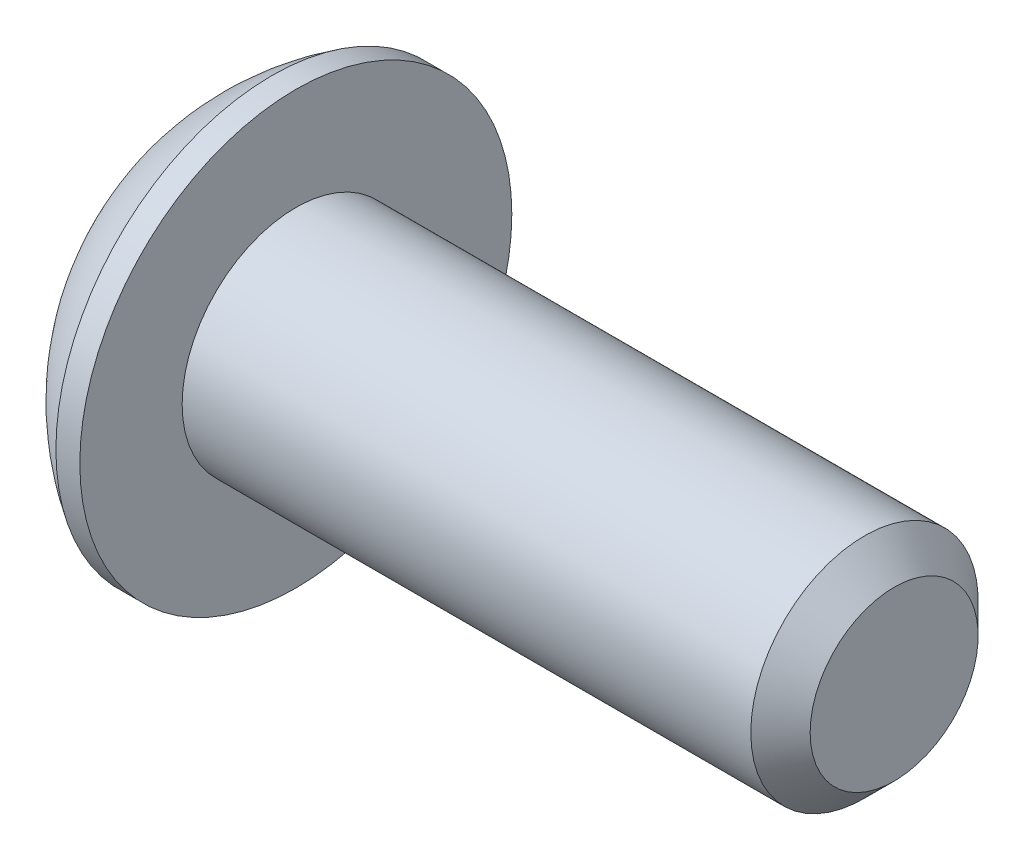
SolidWorks part; units mm, degrees
ref_plane "Plane1" through (0, 0, 0) normal (0, 0, 1) x (1, 0, 0)
ref_plane "Plane2" through (0, 0, 0) normal (0, 1, 0) x (1, 0, 0)
ref_plane "Plane3" through (0, 0, 0) normal (1, 0, 0) x (0, 0, -1)
sketch "BodySke" plane through (0, 0, 0) normal (0, 0, 1) x (1, 0, 0)
  line L0 (15.2654, 0) -> (15.2654, 1.7831)
  line L1 (14.6355, 2.413) -> (2.5654, 2.413)
  line L2 (2.5654, 2.413) -> (2.5654, 4.5847)
  line L3 (2.5654, 4.5847) -> (2.0574, 4.5847)
  line L4 (0, 0) -> (101.6, 0) construction
  line L5 (2.5654, -4.5847) -> (2.0574, -4.5847) construction
  line L6 (55.6768, -2.413) -> (2.5654, -2.413) construction
  line L7 (15.2654, 0) -> (0, 0)
  line L8 (0, 2.2923) -> (0, -2.2923) construction
  line L9 (0, 0) -> (0, 2.2923)
  line L10 (15.2654, 1.7831) -> (14.6355, 2.413)
  line L11 (15.2654, -1.7831) -> (14.6355, -2.413) construction
  line L12 (3.6246, 9.525) -> (3.6246, -2.413) construction
  line L13 (2.5654, 9.525) -> (2.5654, -2.413) construction
  arc A1 (0, 2.2923) -> (2.0574, 4.5847) centre (4.8599, 0) cw
  dimension "D1" = 4.5847
  dimension "Diameter" = 4.826
  dimension "Length" = 12.7
  dimension "Head_dia" = 9.1694
  dimension "Head_ht" = 2.5654
  dimension "Head_side_ht" = 0.508
  dimension "Minor_dia" = 3.5662
  dimension "Body_ch_ang" = 45
  dimension "Advance" = 1.0592
  dimension "Thread_nom" = 12.7
revolve "BaseBody" add sketch "BodySke" angle 360 about L4
cosmetic thread "ThreadCosmetic" [suppressed] parameters "Thread_length"=11.6408, "Thread_minor"=3.5662
sketch "Sketch2" plane through (0, 0, 0) normal (0, 0, 1) x (1, 0, 0)
  line L0 (0, 1.5875) -> (1.778, 1.5875)
  line L1 (1.778, 1.5875) -> (2.6945, 0)
  line L3 (2.6945, 0) -> (0, 0)
  line L4 (0, 0) -> (0, 1.5875)
  line L5 (0, -1.5875) -> (1.778, -1.5875) construction
  line L6 (0, 0) -> (47.625, 0) construction
  dimension "D2" = 60
  dimension "PreBroach_depth" = 1.778
  dimension "PreBroach_dia" = 3.175
revolve "PreBroach" cut sketch "Sketch2" angle 360 about L6
sketch "Sketch3" plane through (0, 0, 0) normal (1, 0, 0) x (0, 0, -1)
  line L0 (-1.5875, -0.9165) -> (-1.5875, 0.9165)
  line L1 (-1.5875, 0.9165) -> (0, 1.8331)
  line L2 (0, 1.8331) -> (1.5875, 0.9165)
  line L3 (1.5875, 0.9165) -> (1.5875, -0.9165)
  line L4 (1.5875, -0.9165) -> (0, -1.8331)
  line L5 (0, -1.8331) -> (-1.5875, -0.9165)
  dimension "D1" = 1.5875
  dimension "D2" = 1.5875
  dimension "D3" = 3.175
  dimension "Hex_size" = 3.175
extrude "Hex" cut sketch "Sketch3" along normal blind 1.778
sketch "Sketch4" plane through (0, 9.525, 0) normal (1, 0, 0) x (0, 0, -1)
  line L0 (0, -9.525) -> (1.8923, -9.525)
  line L1 (0, -9.525) -> (6.1484, -5.9752) construction
  line L2 (0, -9.525) -> (0.9461, -7.8862)
  line L3 (1.5663, -9.09) -> (1.8037, -8.9529)
  line L4 (1.1599, -8.3861) -> (1.3973, -8.249)
  arc A0 (1.5663, -9.09) -> (1.1599, -8.3861) centre (0, -9.525) ccw
  arc A1 (1.8923, -9.525) -> (1.8037, -8.9529) centre (0, -9.525) ccw
  arc A2 (0.9461, -7.8862) -> (1.3973, -8.249) centre (0, -9.525) cw
  dimension "D1" = 30
  dimension "Spline_n_dim" = 3.2512
  dimension "Spline_m_dim" = 3.7846
  dimension "D2" = 60
  dimension "D3" = 0.4064
  dimension "Spline_p_dim" = 0.8128
extrude "Spline" [suppressed] cut sketch "Sketch4" along normal blind 1.778
pattern_circular "CirPattern1" [suppressed] count 6 every 60 about axis through (0, 0, 0) along (1, 0, 0)
sketch "ThdSchSke" plane through (0, 0, 0) normal (0, 0, 1) x (1, 0, 0)
  line L0 (3.6246, -1.7831) -> (3.1835, -2.413)
  line L1 (3.6246, -1.7831) -> (4.0657, -2.413)
  line L2 (4.0657, -2.413) -> (4.0657, -3.0163)
  line L3 (-3.175, 0) -> (5.1513, 0) construction
  line L5 (4.0657, -3.0163) -> (3.1835, -3.0163)
  line L6 (3.1835, -3.0163) -> (3.1835, -2.413)
  dimension "Thread_minor" = 3.5662
  dimension "Diameter" = 4.826
  dimension "Start" = 3.6246
  dimension "SideAngle" = 55
  dimension "VeeAngle" = 70
  dimension "Overcut" = 6.0325
revolve "ThreadSchematic" [suppressed] cut sketch "ThdSchSke" angle 360 about L3
pattern_linear "ThdSchPat" [suppressed]
equation "\"D1@BodySke\" = \"Head_dia@BodySke\" * .5"
equation "\"Thread_minor@ThreadCosmetic\" = \"Minor_dia@BodySke\""
equation "\"D1@Sketch3\" = \"Hex_size@Sketch3\" / 2"
equation "\"D2@Sketch3\" = \"D1@Sketch3\""
equation "\"D3@Sketch3\" = \"Hex_size@Sketch3\""
equation "\"D3@Sketch4\" = \"Spline_p_dim@Sketch4\" / 2"
equation "\"D1@Sketch4\" = \"D2@Sketch4\" / 2"
equation "\"Thread_length@ThreadCosmetic\" = ((sgn( (\"Length@BodySke\" - \"Advance@BodySke\" ) - \"Thread_nom@BodySke\" )-1)*( (\"Length@BodySke\" - \"Advance@BodySke\" ) - \"Thread_nom@BodySke\" ))/-2+ \"Thread_nom@BodySke\""
equation "\"Thread_minor@ThdSchSke\" = \"Minor_dia@BodySke\""
equation "\"Diameter@ThdSchSke\" = \"Diameter@BodySke\""
equation "\"Overcut@ThdSchSke\" = \"Diameter@BodySke\" * 1.25"
equation "\"Start@ThdSchSke\" = \"Head_ht@BodySke\" + \"Length@BodySke\" - \"Thread_length@ThreadCosmetic\"  '---Non-countersunk---"
equation "\"Num_threads@ThdSchPat\" = int( \"Thread_length@ThreadCosmetic\" / \"Advance@BodySke\" + 0.999 )  + 1"
equation "\"Advance@ThdSchPat\" = \"Thread_length@ThreadCosmetic\" /  (\"Num_threads@ThdSchPat\" - 1) 'relax it"
equation "\"Num_threads@ThdSchPat\" = \"Num_threads@ThdSchPat\" - sgn( \"Num_threads@ThdSchPat\" - 1) '---chamfered tips only---"
